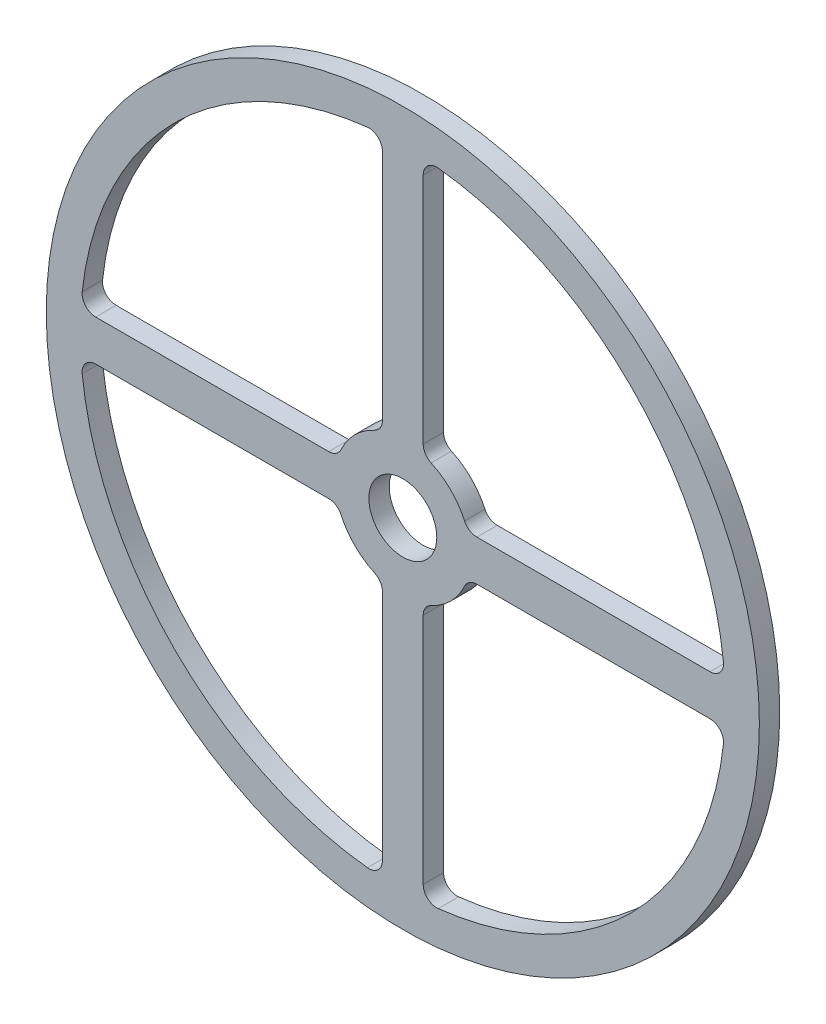
SolidWorks part; units mm, degrees
ref_plane "前视基准面" through (0, 0, 0) normal (0, 0, 1) x (1, 0, 0)
ref_plane "上视基准面" through (0, 0, 0) normal (0, 1, 0) x (1, 0, 0)
ref_plane "右视基准面" through (0, 0, 0) normal (1, 0, 0) x (0, 0, -1)
sketch "草图1" plane through (0, 0, 0) normal (0, 0, 1) x (1, 0, 0)
  line L0 (3, 47.4052) -> (3, 9.5394)
  line L1 (3, -9.5394) -> (3, -47.4052)
  line L2 (0, 61.6672) -> (0, -69.5281) construction
  line L3 (-69.9347, 0) -> (83.2168, 0) construction
  line L4 (-3, 47.4052) -> (-3, 9.5394)
  line L5 (-47.4052, -3) -> (-9.5394, -3)
  line L6 (-47.4052, 3) -> (-9.5394, 3)
  line L7 (9.5394, 3) -> (47.4052, 3)
  line L9 (-3, -9.5394) -> (-3, -47.4052)
  line L10 (9.5394, -3) -> (47.4052, -3)
  circle A0 centre (0, 0) radius 52.5
  arc A1 (-47.4052, -3) -> (-3, -47.4052) centre (0, 0) ccw
  arc A2 (-3, 9.5394) -> (-9.5394, 3) centre (0, 0) ccw
  circle A3 centre (0, 0) radius 5
  arc A4 (3, -9.5394) -> (9.5394, -3) centre (0, 0) ccw
  arc A5 (9.5394, 3) -> (3, 9.5394) centre (0, 0) ccw
  arc A6 (-9.5394, -3) -> (-3, -9.5394) centre (0, 0) ccw
  arc A7 (47.4052, 3) -> (3, 47.4052) centre (0, 0) ccw
  arc A8 (3, -47.4052) -> (47.4052, -3) centre (0, 0) ccw
  arc A9 (-3, 47.4052) -> (-47.4052, 3) centre (0, 0) ccw
  dimension "D1" = 105
  dimension "D2" = 95
  dimension "D3" = 20
  dimension "D4" = 10
  dimension "D5" = 3
  dimension "D6" = 3
extrude "凸台-拉伸1" add sketch "草图1" along normal blind 3
fillet "圆角1" radius 2 16 edges at (9.5394, -3, 1.5) (-47.4052, 3, 1.5) (-47.4052, -3, 1.5) (-9.5394, -3, 1.5) (-3, -9.5394, 1.5) (3, -9.5394, 1.5) (-3, -47.4052, 1.5) (3, -47.4052, 1.5) (-9.5394, 3, 1.5) (-3, 9.5394, 1.5) (3, 9.5394, 1.5) (9.5394, 3, 1.5) (47.4052, -3, 1.5) (47.4052, 3, 1.5) (3, 47.4052, 1.5) (-3, 47.4052, 1.5)
